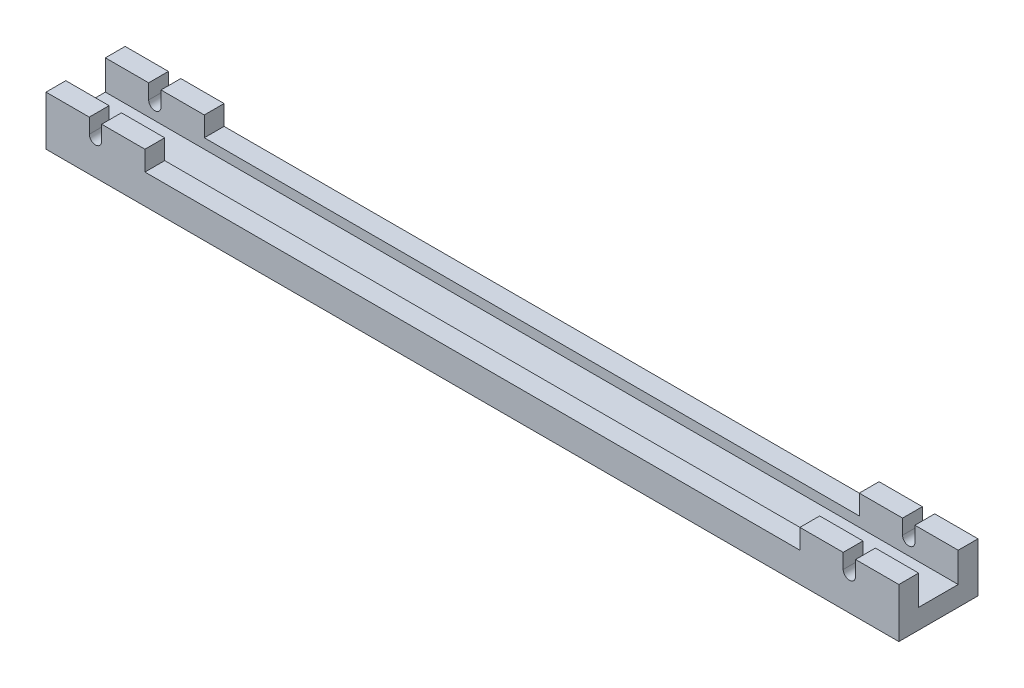
SolidWorks part; units mm, degrees
ref_plane "Front Plane" through (0, 0, 0) normal (0, 0, 1) x (1, 0, 0)
ref_plane "Top Plane" through (0, 0, 0) normal (0, 1, 0) x (1, 0, 0)
ref_plane "Right Plane" through (0, 0, 0) normal (1, 0, 0) x (0, 0, -1)
sketch "Sketch1" plane through (0, 0, 0) normal (0, 1, 0) x (1, 0, 0)
  line L1 (0, 4) -> (43.1, 4)
  line L2 (0, 4) -> (0, -4)
  line L3 (0, -4) -> (43.1, -4)
  line L4 (43.1, 4) -> (43.1, -4)
  point P4 (0, 0)
  dimension "D1" = 43.1
  dimension "D2" = 8
extrude "Boss-Extrude1" add sketch "Sketch1" along normal blind 2
sketch "Sketch2" plane through (0, 2, 0) normal (0, 1, 0) x (1, 0, 0)
  line L9 (43.1, -4) -> (33.1, -4)
  line L10 (43.1, -4) -> (43.1, -2)
  line L11 (43.1, -2) -> (33.1, -2)
  line L12 (33.1, -4) -> (33.1, -2)
  line L13 (43.1, 4) -> (33.1, 4)
  line L14 (43.1, 4) -> (43.1, 2)
  line L15 (43.1, 2) -> (33.1, 2)
  line L16 (33.1, 4) -> (33.1, 2)
  dimension "D1" = 2
  dimension "D2" = 10
extrude "Boss-Extrude2" add sketch "Sketch2" along normal blind 3
sketch "Sketch3" plane through (0, 2, 0) normal (0, 1, 0) x (1, 0, 0)
  line L1 (0, -4) -> (33.1, -4)
  line L2 (0, -4) -> (0, -2)
  line L3 (0, -2) -> (33.1, -2)
  line L4 (33.1, -4) -> (33.1, -2)
  line L5 (0, 4) -> (33.1, 4)
  line L6 (0, 4) -> (0, 2)
  line L7 (0, 2) -> (33.1, 2)
  line L8 (33.1, 4) -> (33.1, 2)
extrude "Boss-Extrude3" add sketch "Sketch3" along normal blind 1
sketch "Sketch4" plane through (0, 0, 4) normal (0, 0, 1) x (1, 0, 0)
  line L1 (37.475, 3.5) -> (37.475, 5)
  line L2 (33.1, 5) -> (43.1, 5) construction
  line L3 (38.725, 3.5) -> (38.725, 5)
  line L4 (38.725, 5) -> (37.475, 5)
  line L5 (43.1, 2) -> (0, 2) construction
  arc A0 (37.475, 3.5) -> (38.725, 3.5) centre (38.1, 3.5) ccw
  dimension "D1" = 1.25
  dimension "D2" = 38.1
  dimension "D3" = 1.5
extrude "Cut-Extrude1" cut sketch "Sketch4" against normal through all
mirror "Mirror1" about plane through (0, 0, 0) normal (1, 0, 0) of "Cut-Extrude1", "Boss-Extrude3", "Boss-Extrude2", "Boss-Extrude1"
equation "\"SPACING\"= 3in"
equation "\"D1@Sketch1\"=\"SPACING\"/2+5"
equation "\"WIREDIA\"= 1.25mm"
equation "\"D1@Sketch4\"=\"WIREDIA\""
equation "\"D2@Sketch4\"=\"SPACING\"/2"
